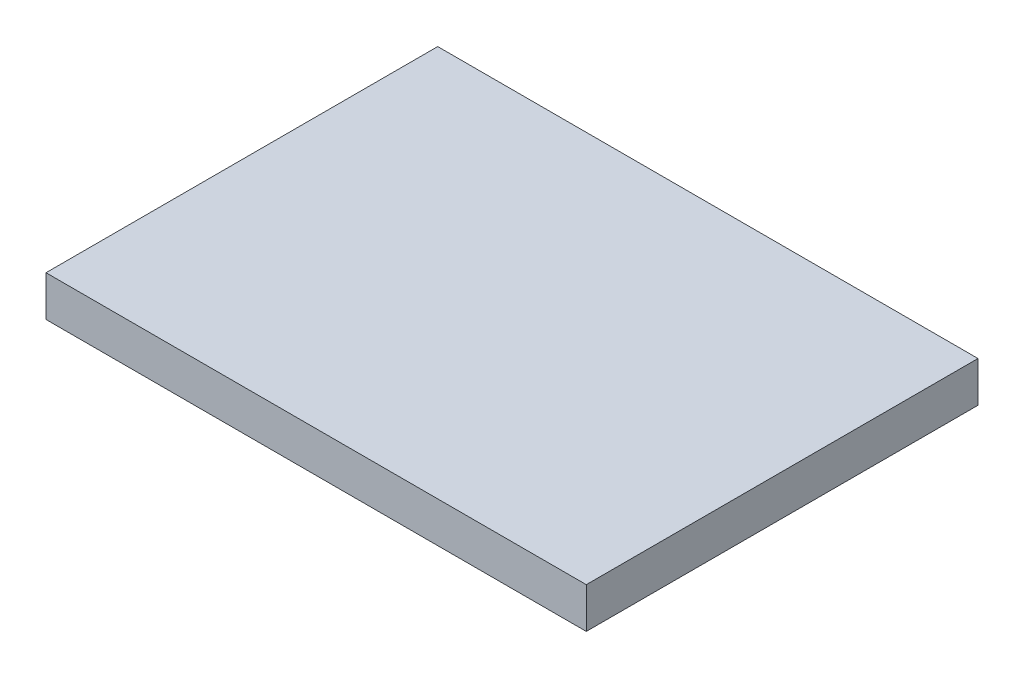
SolidWorks part; units mm, degrees
material "Acrylic (Medium-high impact)"
ref_plane "Front Plane" through (0, 0, 0) normal (0, 0, 1) x (1, 0, 0)
ref_plane "Top Plane" through (0, 0, 0) normal (0, 1, 0) x (1, 0, 0)
ref_plane "Right Plane" through (0, 0, 0) normal (1, 0, 0) x (0, 0, -1)
sketch "Sketch1" plane through (0, 0, 0) normal (0, 1, 0) x (1, 0, 0)
  line L1 (-40, 29) -> (40, 29)
  line L2 (-40, 29) -> (-40, -29)
  line L3 (-40, -29) -> (40, -29)
  line L4 (40, 29) -> (40, -29)
  line L5 (-40, 29) -> (40, -29) construction
  line L6 (-40, -29) -> (40, 29) construction
  point P0 (0, 0)
  dimension "D1" = 80
  dimension "D2" = 58
extrude "Boss-Extrude1" add sketch "Sketch1" along normal blind 6 contours L2 L3 L4 L1
